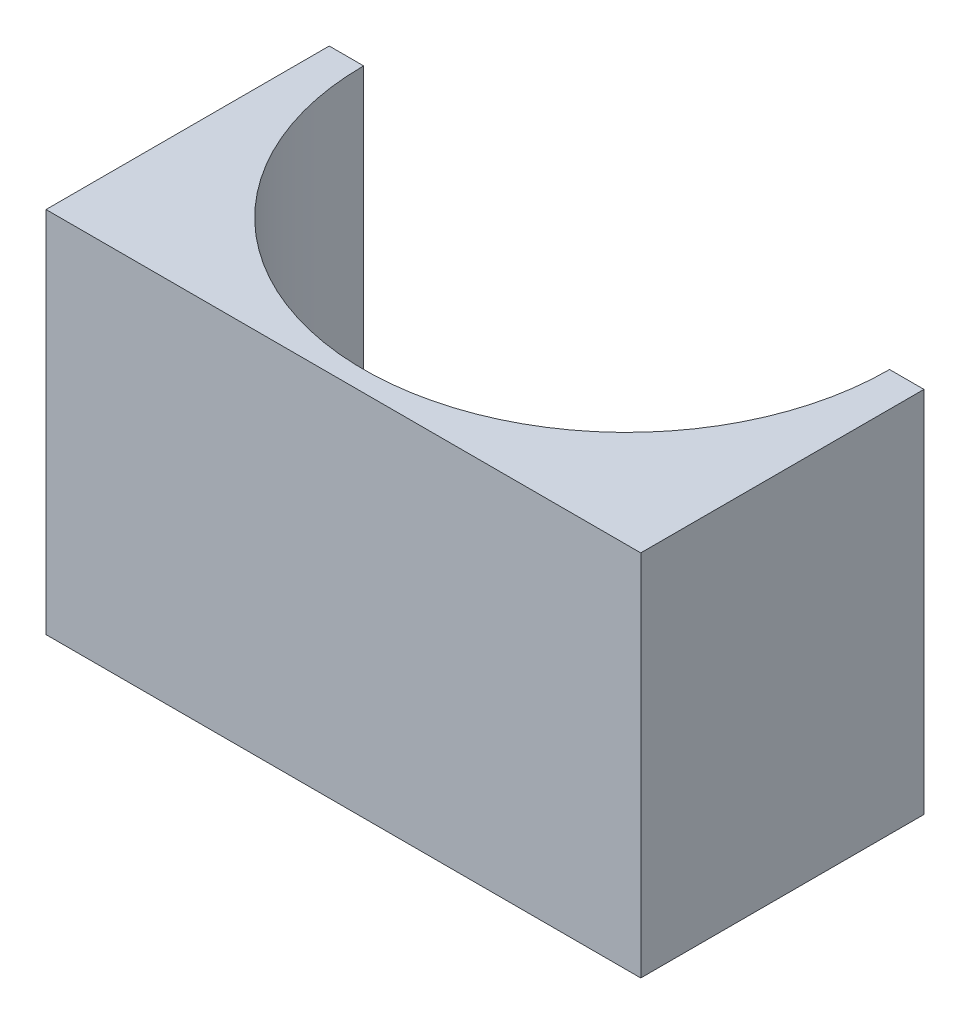
SolidWorks part; units mm, degrees
ref_plane "Front Plane" through (0, 0, 0) normal (0, 0, 1) x (1, 0, 0)
ref_plane "Top Plane" through (0, 0, 0) normal (0, 1, 0) x (1, 0, 0)
ref_plane "Right Plane" through (0, 0, 0) normal (1, 0, 0) x (0, 0, -1)
sketch "Sketch1" plane through (0, 0, 0) normal (0, 1, 0) x (1, 0, 0)
  line L1 (-36.75, 17.5) -> (36.75, 17.5)
  line L2 (-36.75, 17.5) -> (-36.75, -17.5)
  line L3 (-36.75, -17.5) -> (36.75, -17.5)
  line L4 (36.75, 17.5) -> (36.75, -17.5)
  line L5 (-36.75, 17.5) -> (36.75, -17.5) construction
  line L6 (-36.75, -17.5) -> (36.75, 17.5) construction
  point P0 (0, 0)
  dimension "D1" = 35
  dimension "D2" = 73.5
extrude "Boss-Extrude1" add sketch "Sketch1" along normal blind 45.5 contours L2 L1 L4 L3
sketch "Sketch2" plane through (0, 45.5, 0) normal (0, 1, 0) x (1, 0, 0)
  line L0 (-36.75, 17.5) -> (36.75, 17.5) construction
  circle A0 centre (0, 17.5) radius 32.5
extrude "Cut-Extrude1" cut sketch "Sketch2" against normal through all
